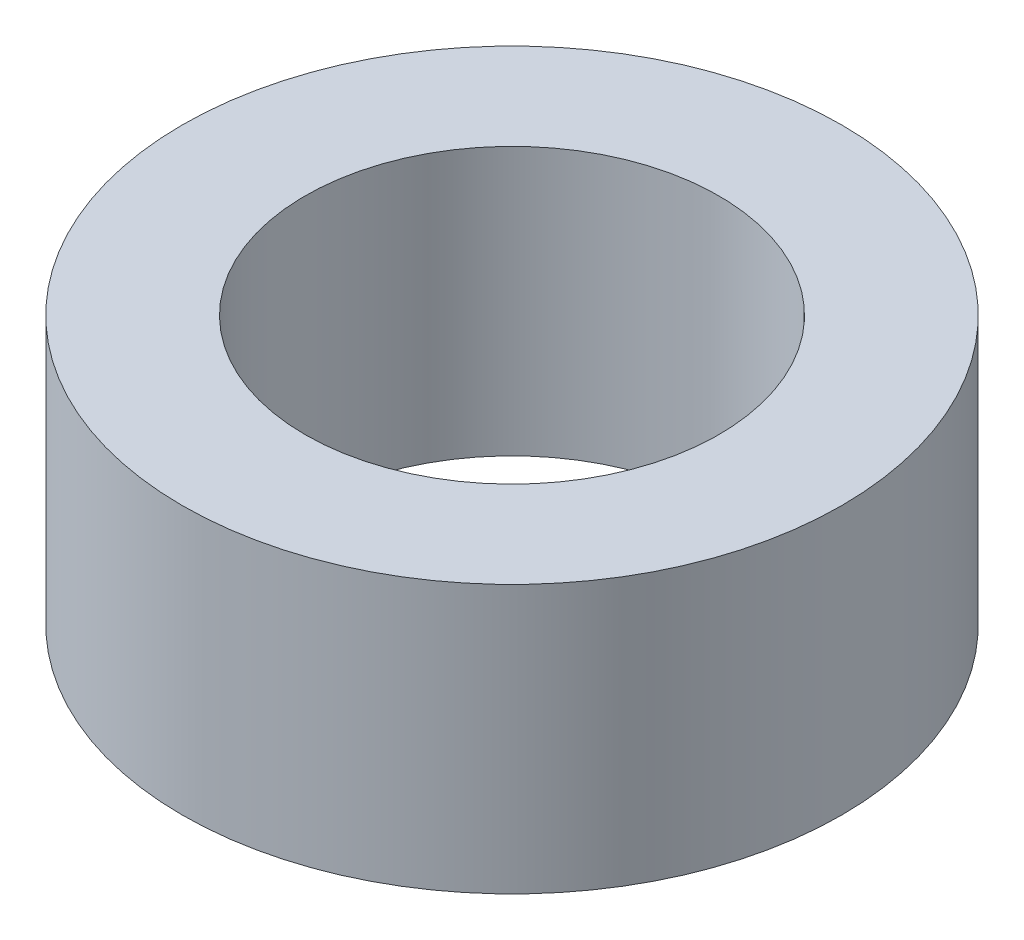
SolidWorks part; units mm, degrees
ref_plane "Front" through (0, 0, 0) normal (0, 0, 1) x (1, 0, 0)
ref_plane "Top" through (0, 0, 0) normal (0, 1, 0) x (1, 0, 0)
ref_plane "Right" through (0, 0, 0) normal (1, 0, 0) x (0, 0, -1)
sketch "Sketch1" plane through (0, 0, 0) normal (0, 1, 0) x (1, 0, 0)
  circle A0 centre (0, 0) radius 2.19
  circle A1 centre (0, 0) radius 3.69
  dimension "D1" = 1.5
extrude "Boss-Extrude3" add sketch "Sketch1" along normal blind 3 contours A1
sketch "Sketch3" plane through (0, 3, 0) normal (0, 1, 0) x (1, 0, 0)
  circle A0 centre (0, 0) radius 2.0065
extrude "Cut-Extrude2" cut sketch "Sketch3" against normal blind 3
sketch "Sketch4" plane through (0, 3, 0) normal (0, 1, 0) x (1, 0, 0)
  circle A0 centre (0, 0) radius 2.3153
extrude "Cut-Extrude3" cut sketch "Sketch4" against normal blind 3
